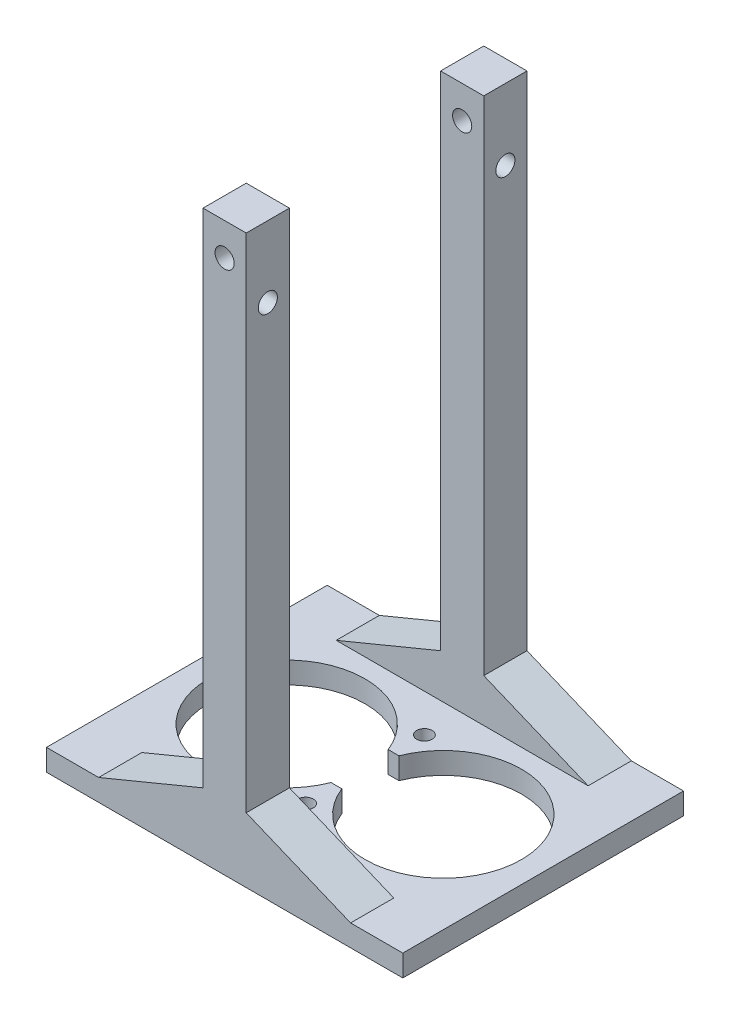
SolidWorks part; units mm, degrees
ref_plane "Front Plane" through (0, 0, 0) normal (0, 0, 1) x (1, 0, 0)
ref_plane "Top Plane" through (0, 0, 0) normal (0, 1, 0) x (1, 0, 0)
ref_plane "Right Plane" through (0, 0, 0) normal (1, 0, 0) x (0, 0, -1)
sketch "Sketch1" plane through (0, 0, 0) normal (0, 1, 0) x (1, 0, 0)
  line L0 (-22.9246, -15.0545) -> (-20.9246, -15.0545) construction
  line L1 (-36.4246, -27.5545) -> (-7.4246, -27.5545)
  line L2 (-36.4246, 8.4455) -> (-7.4246, 8.4455)
  line L3 (-36.4246, 8.4455) -> (-54.9246, 8.4455)
  line L4 (-54.9246, 8.4455) -> (-54.9246, -27.5545)
  line L5 (-20.9246, -15.0545) -> (-20.9246, -4.0545) construction
  line L6 (-20.9246, -4.0545) -> (-22.9246, -4.0545) construction
  line L7 (-22.9246, -4.0545) -> (-22.9246, -15.0545) construction
  line L8 (-22.9246, -9.5545) -> (-36.4246, -9.5545) construction
  line L9 (-20.9246, -9.5545) -> (-7.4246, -9.5545) construction
  line L10 (-22.9246, -4.263) -> (-20.9246, -4.263)
  line L11 (-20.9246, -4.263) -> (-21.0219, -4.2437)
  line L12 (-22.9246, -14.846) -> (-20.9246, -14.846)
  line L13 (-54.9246, -27.5545) -> (-36.4246, -27.5545)
  line L14 (-7.4246, 8.4455) -> (11.0754, 8.4455)
  line L15 (-7.4246, -27.5545) -> (11.0754, -27.5545)
  line L16 (11.0754, -27.5545) -> (11.0754, 8.4455)
  arc A0 (-22.9246, -4.263) -> (-22.9246, -14.846) centre (-36.4246, -9.5545) ccw
  arc A1 (-20.9246, -14.846) -> (-20.9246, -4.263) centre (-7.4246, -9.5545) ccw
  dimension "D1" = 29
  dimension "D5" = 32
  dimension "D2" = 29
  dimension "D3" = 11
  dimension "D4" = 2
  dimension "D6" = 32
  dimension "D7" = 36
extrude "Boss-Extrude1" add sketch "Sketch1" along normal blind 4
sketch "Sketch3" plane through (0, 0, 0) normal (0, -1, 0) x (1, 0, 0)
  line L0 (-21.9246, 9.5545) -> (-36.4246, 9.5545) construction
  line L1 (-21.9246, -1.4455) -> (-21.9246, 20.5545) construction
  line L2 (-21.9246, 9.5545) -> (-7.4246, 9.5545) construction
  circle A0 centre (-21.9246, -1.4455) radius 1.4272
  circle A1 centre (-21.9246, 20.5545) radius 1.4272
  arc A4 (-22.9246, 14.846) -> (-22.9246, 4.263) centre (-36.4246, 9.5545) ccw construction
  arc A5 (-20.9246, 4.263) -> (-20.9246, 14.846) centre (-7.4246, 9.5545) ccw construction
  dimension "D1" = 22
extrude "Cut-Extrude1" cut sketch "Sketch3" against normal through all
sketch "Sketch4" plane through (0, 0, 0) normal (0, -1, 0) x (1, 0, 0)
  line L0 (-54.9246, -8.4455) -> (11.0754, -8.4455) construction
  line L1 (-25.9246, -8.4455) -> (-17.9246, -8.4455)
  line L2 (-25.9246, -8.4455) -> (-25.9246, -16.4455)
  line L3 (-25.9246, -16.4455) -> (-17.9246, -16.4455)
  line L4 (-17.9246, -8.4455) -> (-17.9246, -16.4455)
  line L5 (-54.9246, 27.5545) -> (11.0754, 27.5545) construction
  line L6 (-25.9246, 27.5545) -> (-17.9246, 27.5545)
  line L7 (-25.9246, 27.5545) -> (-25.9246, 35.5545)
  line L8 (-25.9246, 35.5545) -> (-17.9246, 35.5545)
  line L9 (-17.9246, 27.5545) -> (-17.9246, 35.5545)
  line L10 (-21.9246, -16.7232) -> (-21.9246, 33.8196) construction
  dimension "D1" = 8
extrude "Boss-Extrude3" add sketch "Sketch4" against normal blind 105
sketch "Sketch5" plane through (0, 0, 35.5545) normal (0, 0, 1) x (1, 0, 0)
  line L0 (-21.9246, 105) -> (-21.9246, 90.3449) construction
  line L1 (-17.9246, 105) -> (-25.9246, 105) construction
  circle A0 centre (-21.9246, 99) radius 1.775
  dimension "D1" = 3.55
  dimension "D2" = 6
extrude "Cut-Extrude2" cut sketch "Sketch5" against normal up to surface (52 mm away) up to face at (-21.9246, 52.5, -16.4455)
sketch "Sketch6" plane through (-17.9246, 0, 0) normal (1, 0, 0) x (0, 0, -1)
  line L0 (-35.5545, 91.8395) -> (-31.5545, 91.8395) construction
  line L2 (-35.5545, 105) -> (-35.5545, 0) construction
  line L4 (-31.5545, 91.8395) -> (-27.5545, 91.8395) construction
  line L6 (-27.5545, 105) -> (-27.5545, 4) construction
  line L9 (8.4455, 105) -> (8.4455, 4) construction
  line L10 (8.4455, 91.8395) -> (12.4455, 91.8395) construction
  line L11 (12.4455, 91.8395) -> (16.4455, 91.8395) construction
  line L12 (16.4455, 105) -> (16.4455, 0) construction
  circle A0 centre (-31.5545, 91.8395) radius 1.775
  circle A1 centre (12.4455, 91.8395) radius 1.775
  point P4 (0, 0)
  point P17 (0, 0)
  dimension "D1" = 3.55
  dimension "D2" = 44
extrude "Cut-Extrude3" cut sketch "Sketch6" against normal through all
sketch "Sketch7" plane through (0, 0, 27.5545) normal (0, 0, 1) x (1, 0, 0)
  line L0 (-45.258, 4) -> (-25.9246, 12)
  line L1 (-25.9246, 105) -> (-25.9246, 0) construction
  line L2 (-25.9246, 12) -> (-25.9246, 0)
  line L3 (-25.9246, 0) -> (-54.9246, 0)
  line L4 (-17.9246, 0) -> (-17.9246, 12)
  line L5 (-17.9246, 105) -> (-17.9246, 0) construction
  line L6 (-17.9246, 12) -> (1.4087, 4)
  line L7 (11.0754, 0) -> (-17.9246, 0)
  line L8 (-54.9246, 0) -> (-54.9246, 4)
  line L9 (-54.9246, 4) -> (-45.258, 4)
  line L10 (11.0754, 0) -> (11.0754, 4)
  line L11 (11.0754, 4) -> (1.4087, 4)
  dimension "D1" = 12
extrude "Boss-Extrude4" add sketch "Sketch7" along normal up to surface (8 mm away) up to face at (-20.1496, 99, 35.5545)
sketch "Sketch8" plane through (0, 0, -8.4455) normal (0, 0, -1) x (-1, 0, 0)
  line L0 (-11.0754, 0) -> (-11.0754, 4)
  line L1 (-11.0754, 4) -> (-1.4087, 4)
  line L2 (-1.4087, 4) -> (17.9246, 12)
  line L3 (17.9246, 12) -> (17.9246, 0)
  line L4 (17.9246, 0) -> (-11.0754, 0)
  line L5 (25.9246, 12) -> (45.258, 4)
  line L6 (25.9246, 105) -> (25.9246, 0) construction
  line L7 (45.258, 4) -> (54.9246, 4)
  line L8 (54.9246, 4) -> (54.9246, 0)
  line L9 (54.9246, 0) -> (25.9246, 0)
  line L10 (25.9246, 0) -> (25.9246, 12)
extrude "Boss-Extrude5" add sketch "Sketch8" along normal up to surface (8 mm away) up to face at (-23.6996, 99, -16.4455)
